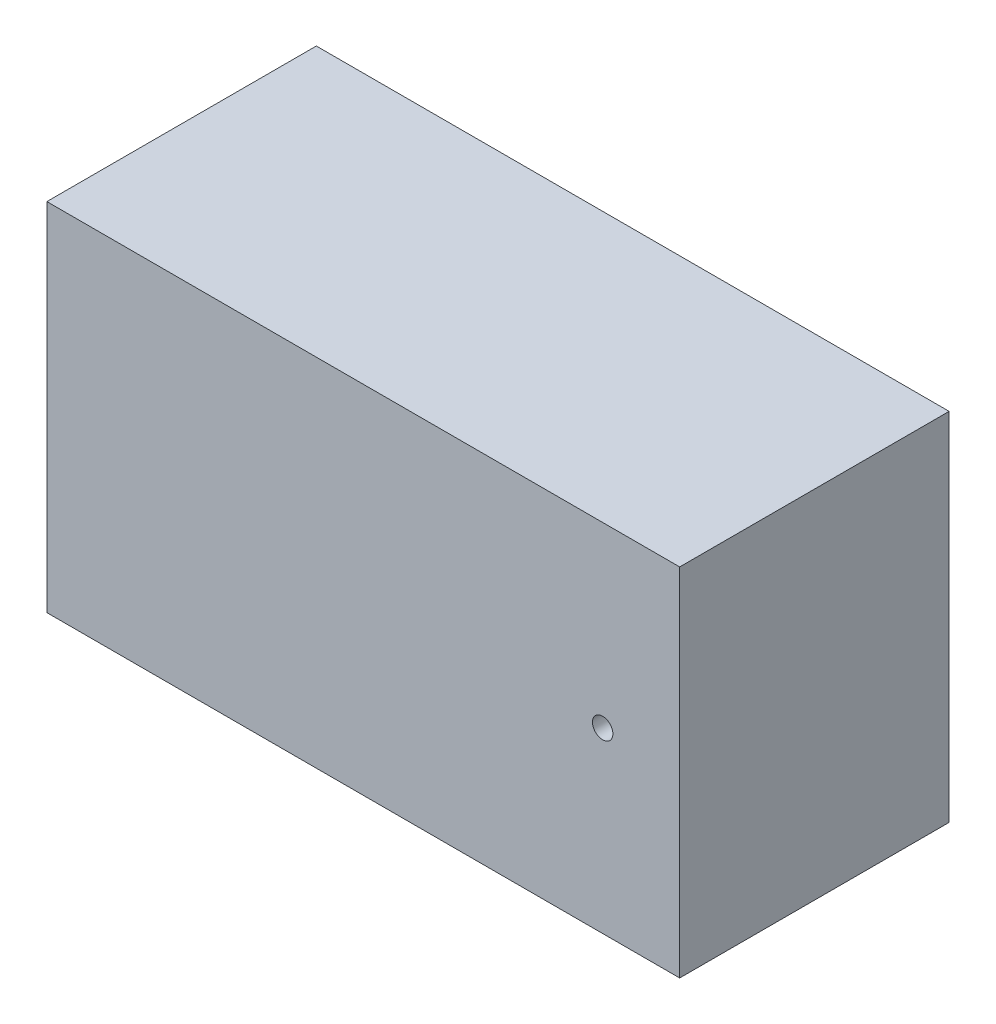
SolidWorks part; units mm, degrees
ref_plane "Ön Düzlem" through (0, 0, 0) normal (0, 0, 1) x (1, 0, 0)
ref_plane "Üst Düzlem" through (0, 0, 0) normal (0, 1, 0) x (1, 0, 0)
ref_plane "Sağ Düzlem" through (0, 0, 0) normal (1, 0, 0) x (0, 0, -1)
sketch "Çizim1" plane through (0, 0, 0) normal (0, 0, 1) x (1, 0, 0)
  line L1 (-77.5, 43.6) -> (77.5, 43.6)
  line L2 (-77.5, 43.6) -> (-77.5, -43.6)
  line L3 (-77.5, -43.6) -> (77.5, -43.6)
  line L9 (77.5, 43.6) -> (77.5, -43.6)
  point P1 (-77.5, 0)
  point P7 (0, 43.6)
  point P11 (0, -43.6)
  dimension "D1" = 155
  dimension "D2" = 87.2
extrude "Yükseklik-Ekstrüzyon1" add sketch "Çizim1" along normal blind 66
sketch "Çizim2" plane through (0, 0, 66) normal (0, 0, 1) x (1, 0, 0)
  line L0 (-77.5, 43.6) -> (-77.5, -43.6) construction
  line L2 (-77.5, -43.6) -> (77.5, -43.6) construction
  circle A0 centre (58.64, 0) radius 2.5
  dimension "D3" = 5
  dimension "D1" = 136.14
  dimension "D2" = 43.6
extrude "Kes-Ekstrüzyon1" cut sketch "Çizim2" against normal through all
sketch "Çizim3" plane through (-77.5, 0, 0) normal (-1, 0, 0) x (0, 0, 1)
  line L0 (66, 43.6) -> (66, -43.6) construction
  line L1 (13, 20) -> (53, 20)
  line L2 (13, 20) -> (13, -20)
  line L3 (13, -20) -> (53, -20)
  line L4 (53, 20) -> (53, -20)
  line L6 (66, -43.6) -> (0, -43.6) construction
  line L8 (66, 43.6) -> (0, 43.6) construction
  dimension "D1" = 13
  dimension "D2" = 40
  dimension "D3" = 23.6
  dimension "D4" = 23.6
extrude "Kes-Ekstrüzyon2" cut sketch "Çizim3" against normal blind 112
